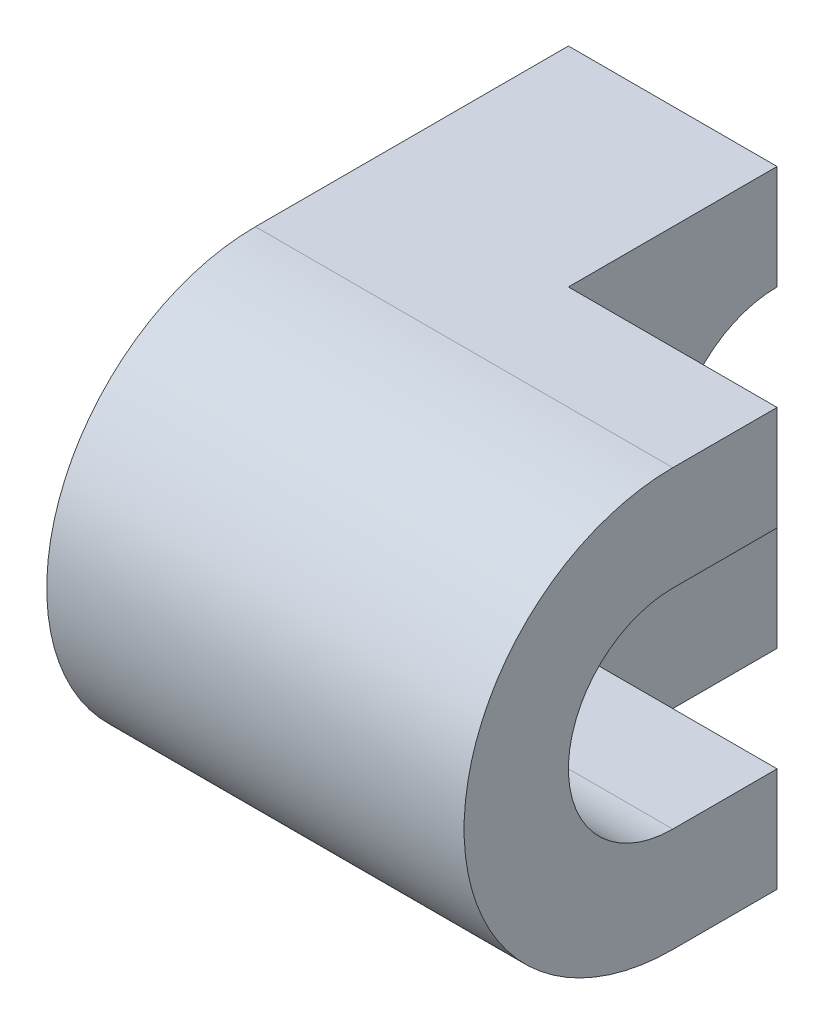
SolidWorks part; units mm, degrees
ref_plane "Front Plane" through (0, 0, 0) normal (0, 0, 1) x (1, 0, 0)
ref_plane "Top Plane" through (0, 0, 0) normal (0, 1, 0) x (1, 0, 0)
ref_plane "Right Plane" through (0, 0, 0) normal (1, 0, 0) x (0, 0, -1)
sketch "Sketch1" plane through (0, 0, 0) normal (1, 0, 0) x (0, 0, -1)
  line L0 (0, 20) -> (30, 20)
  line L1 (30, 20) -> (30, 10)
  line L2 (30, -20) -> (0, -20)
  line L3 (30, -10) -> (30, -20)
  arc A0 (0, 20) -> (0, -20) centre (0, 0) ccw
  arc A1 (30, 10) -> (30, -10) centre (30, 0) ccw
  dimension "D1" = 40
  dimension "D2" = 30
extrude "Boss-Extrude1" add sketch "Sketch1" along normal blind 20
sketch "Sketch2" plane through (20, 0, 0) normal (1, 0, 0) x (0, 0, -1)
  line L0 (0, 20) -> (10, 20)
  line L1 (30, 20) -> (0, 20) construction
  line L2 (10, 20) -> (10, 10)
  line L3 (0, -20) -> (30, -20) construction
  line L4 (10, -20) -> (0, -20)
  line L5 (0, 10) -> (10, 10)
  line L6 (0, -10) -> (10, -10)
  line L7 (10, -10) -> (10, -20)
  arc A0 (0, 20) -> (0, -20) centre (0, 0) ccw
  arc A1 (0, 10) -> (0, -10) centre (0, 0) ccw
  dimension "D1" = 40
  dimension "D2" = 20
  dimension "D3" = 10
extrude "Boss-Extrude2" add sketch "Sketch2" along normal blind 20
